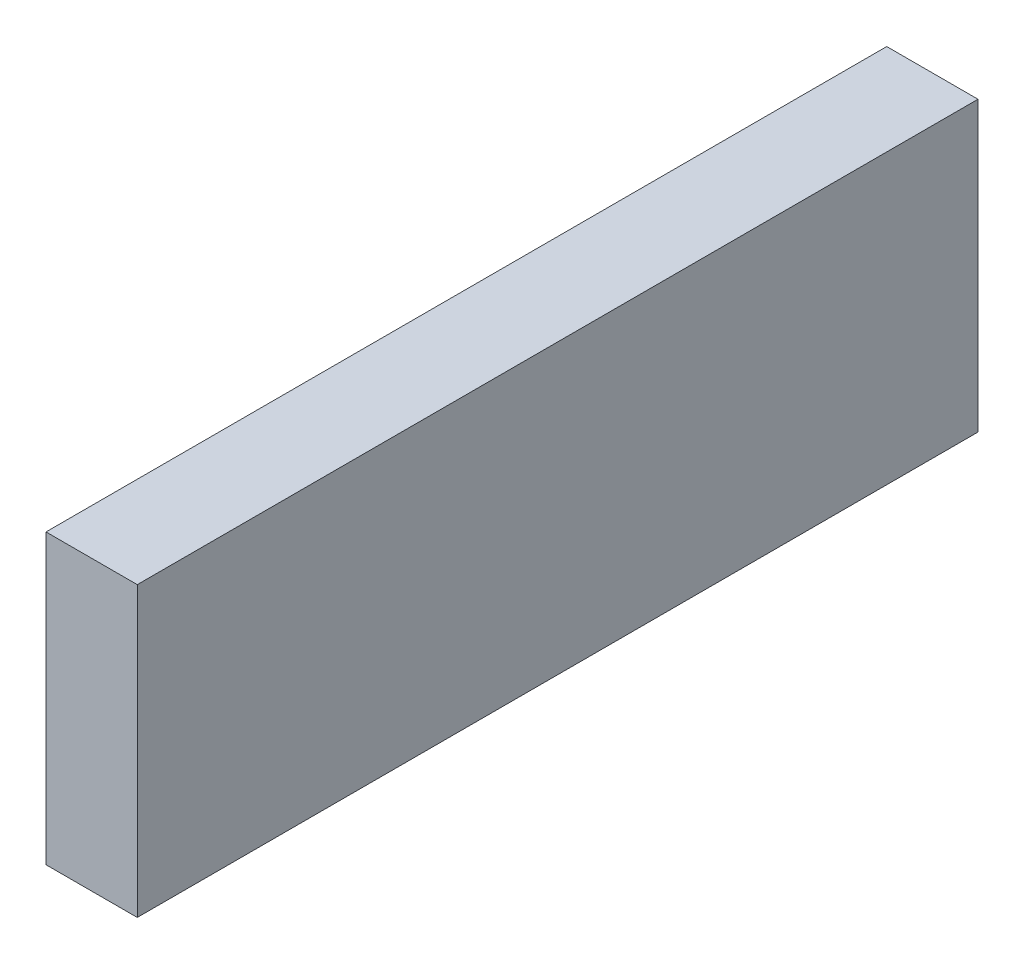
SolidWorks part; units mm, degrees
material "Balsa"
ref_plane "Front Plane" through (0, 0, 0) normal (0, 0, 1) x (1, 0, 0)
ref_plane "Top Plane" through (0, 0, 0) normal (0, 1, 0) x (1, 0, 0)
ref_plane "Right Plane" through (0, 0, 0) normal (1, 0, 0) x (0, 0, -1)
sketch "Sketch1" plane through (0, 0, 0) normal (1, 0, 0) x (0, 0, -1)
  line L0 (-87.5, -30) -> (87.5, 30) construction
  line L1 (-87.5, -30) -> (87.5, -30)
  line L2 (-87.5, -30) -> (-87.5, 30)
  line L3 (-87.5, 30) -> (87.5, 30)
  line L4 (87.5, -30) -> (87.5, 30)
  line L5 (-87.5, 30) -> (87.5, -30) construction
  point P4 (0, 0)
  point P5 (0, 0)
  dimension "D1" = 175
  dimension "D2" = 60
extrude "Boss-Extrude1" add sketch "Sketch1" along normal blind 19
